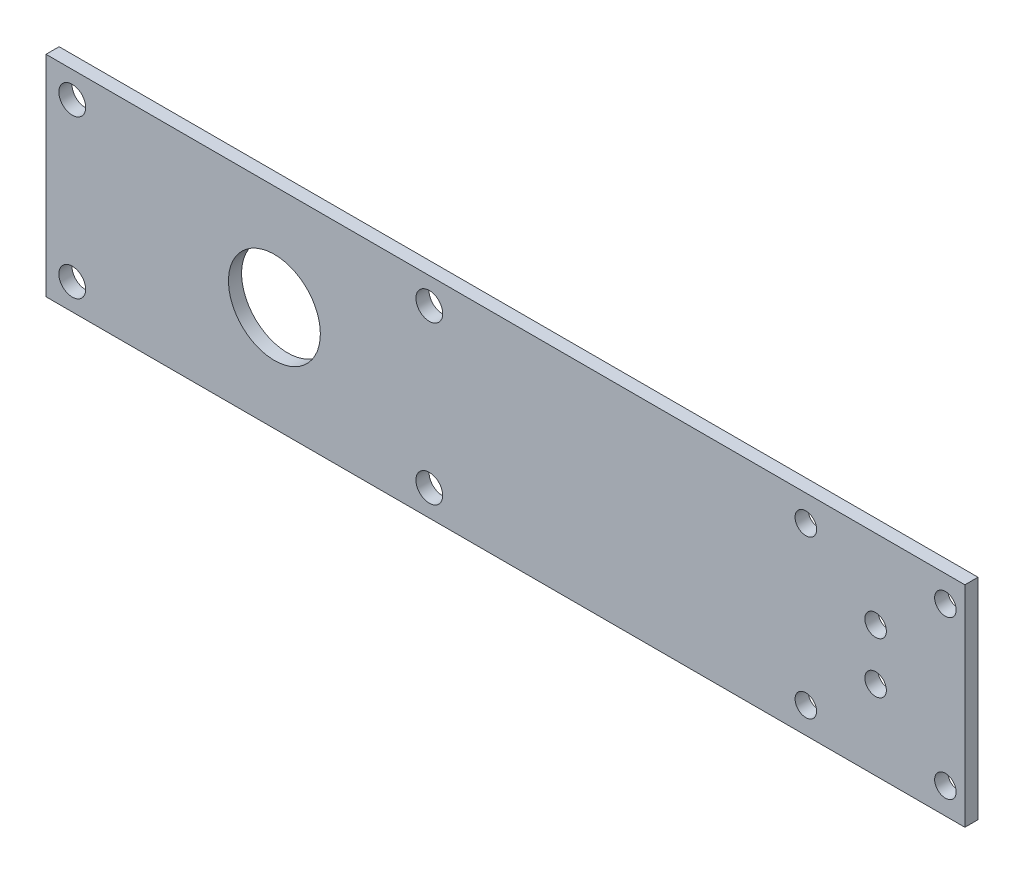
SolidWorks part; units mm, degrees
ref_plane "Front Plane" through (0, 0, 0) normal (0, 0, 1) x (1, 0, 0)
ref_plane "Top Plane" through (0, 0, 0) normal (0, 1, 0) x (1, 0, 0)
ref_plane "Right Plane" through (0, 0, 0) normal (1, 0, 0) x (0, 0, -1)
sketch "Sketch1" plane through (0, 0, 0) normal (0, 0, 1) x (1, 0, 0)
  line L7 (27.4154, 0) -> (-27.4154, 0) construction
  line L12 (263, -40) -> (-87, -40)
  line L13 (263, -40) -> (263, 40)
  line L14 (263, 40) -> (-87, 40)
  line L15 (-87, -40) -> (-87, 40)
  line L16 (263, -40) -> (-87, 40) construction
  line L17 (263, 40) -> (-87, -40) construction
  line L18 (0, -16.055) -> (0, 16.055) construction
  point P0 (88, 0)
  dimension "D1" = 350
  dimension "D2" = 80
  dimension "D3" = 87
extrude "Boss-Extrude1" add sketch "Sketch1" along normal blind 5
extrude "Cut-Extrude1" cut sketch "Sketch2" along normal blind 60
sketch "Sketch2" plane through (211.3258, -35.2622, -13.2427) normal (0, 0, 1) x (1, 0, 0)
  line L0 (-191.5137, 35.2622) -> (-231.1379, 35.2622) construction
  circle A5 centre (-211.3258, 35.2622) radius 17.5
  dimension "D1" = 35
extrude "Cut-Extrude2" cut sketch "Sketch3" along normal blind 10
sketch "Sketch3" plane through (20.8195, -63.6397, 0) normal (0, 0, 1) x (1, 0, 0)
  line L1 (-1.0074, 63.6397) -> (-40.6316, 63.6397) construction
  line L2 (154.1805, 63.6397) -> (-195.8195, 63.6397) construction
  line L3 (154.1805, 23.6397) -> (154.1805, 103.6397) construction
  line L4 (-195.8195, 103.6397) -> (-195.8195, 23.6397) construction
  line L5 (-20.8195, 54.6861) -> (-20.8195, 72.5933) construction
  circle A0 centre (-97.8195, 93.6397) radius 5.1
  circle A1 centre (38.1805, 33.6397) radius 5.1
  circle A3 centre (38.1805, 93.6397) radius 5.1
  circle A4 centre (-97.8195, 33.6397) radius 5.1
  point P1 (134.1805, 63.6397)
  dimension "D1" = 10.2
  dimension "D2" = 60
  dimension "D3" = 77
  dimension "D4" = 136
sketch "Sketch5" plane through (0, 0, 0) normal (0, 0, 1) x (1, 0, 0)
  line L0 (263, -40) -> (263, 40) construction
  line L1 (263, 0) -> (-87, 0) construction
  line L2 (-87, 40) -> (-87, -40) construction
  line L3 (229, 9.75) -> (229, -9.75) construction
  circle A0 centre (229, 9.75) radius 4.1
  circle A1 centre (229, -9.75) radius 4.1
  point P4 (229, 0)
  dimension "D2" = 8.2
  dimension "D1" = 34
  dimension "D4" = 19.5
extrude "Cut-Extrude3" cut sketch "Sketch5" along normal through all
sketch "Sketch7" plane through (0, 0, 0) normal (0, 0, 1) x (1, 0, 0)
  line L0 (19.8121, 0) -> (-19.8121, 0) construction
  line L2 (-87, -40) -> (263, -40) construction
  line L3 (263, 40) -> (195, 40) construction
  line L4 (263, 40) -> (263, -40) construction
  line L5 (263, -40) -> (195, -40) construction
  line L6 (195, 40) -> (195, -40) construction
  line L7 (229, 40) -> (229, -40) construction
  circle A0 centre (202.42, 30) radius 4.1
  circle A1 centre (202.42, -30) radius 4.1
  circle A2 centre (255.58, -30) radius 4.1
  circle A3 centre (255.58, 30) radius 4.1
  dimension "D1" = 8.2
  dimension "D2" = 30
  dimension "D3" = 68
extrude "Cut-Extrude5" cut sketch "Sketch7" along normal through all
